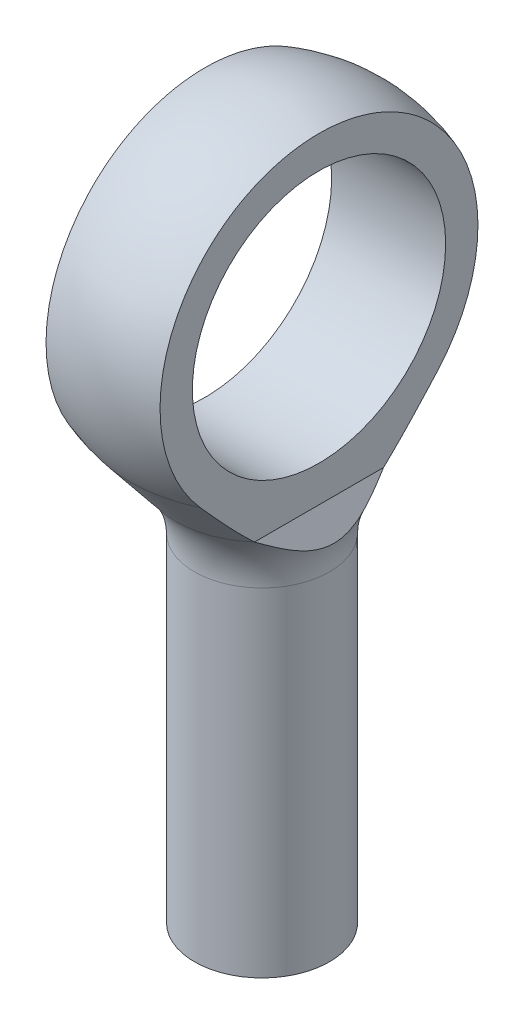
SolidWorks part; units mm, degrees
ref_plane "Front Plane" through (0, 0, 0) normal (0, 0, 1) x (1, 0, 0)
ref_plane "Top Plane" through (0, 0, 0) normal (0, 1, 0) x (1, 0, 0)
ref_plane "Right Plane" through (0, 0, 0) normal (1, 0, 0) x (0, 0, -1)
sketch "Sketch1" plane through (0, 0, 0) normal (0, 0, 1) x (1, 0, 0)
  line L0 (0, 0) -> (0, 7819.097) construction
  line L1 (5.0982, 23.1266) -> (7.8037, 26.5029)
  line L2 (4, 0) -> (-4, 0) construction
  line L3 (4, 0) -> (4, 20)
  line L4 (4, 21.7562) -> (-4, 21.7562) construction
  line L5 (-4, 0) -> (-4, 20)
  line L6 (-5.0982, 23.1266) -> (-7.8037, 26.5029)
  line L7 (0, 42.7562) -> (0, 0)
  line L8 (-4, 0) -> (4, 0)
  arc A0 (7.8037, 26.5029) -> (-7.8037, 26.5029) centre (0, 32.7562) ccw
  arc A1 (4, 20) -> (5.0982, 23.1266) centre (9, 20) cw
  arc A2 (-4, 20) -> (-5.0982, 23.1266) centre (-9, 20) ccw
  point P7 (0, 0)
  dimension "D1" = 20
  dimension "D5" = 5
  dimension "D2" = 8
  dimension "D3" = 20
  dimension "D4" = 11
revolve "Revolve2" add sketch "Sketch1" angle 360 about L0
sketch "Sketch2" plane through (0, 0, 0) normal (0, 0, 1) x (1, 0, 0)
  line L0 (-20, 42.7562) -> (20, 42.7562)
  line L1 (20, 42.7562) -> (20, -5.6687)
  line L2 (20, -5.6687) -> (3.375, 23.1266)
  line L3 (3.375, 23.1266) -> (3.375, 42.7562)
  line L4 (-20, 42.7562) -> (-20, -5.6687)
  line L5 (-20, -5.6687) -> (-3.375, 23.1266)
  line L6 (-3.375, 23.1266) -> (-3.375, 42.7562)
  line L7 (0, 0) -> (0, 50000) construction
  line L8 (-4, 0) -> (4, 0) construction
  line L9 (5.0982, 23.1266) -> (-5.0982, 23.1266) construction
  arc A0 (7.8037, 26.5029) -> (-7.8037, 26.5029) centre (0, 32.7562) ccw construction
  point P23 (0, 0)
  dimension "D1" = 3.375
  dimension "D2" = 3.375
  dimension "D3" = 150
  dimension "D4" = 150
  dimension "D5" = 40
  dimension "D6" = 20
extrude "Cut-Extrude4" cut sketch "Sketch2" against normal through all both and the other way through all contours L5 L6 L0 L4 | L3 L2 L1 L0
sketch "Sketch3" plane through (3.375, 0, 0) normal (1, 0, 0) x (0, 0, -1)
  line L0 (0, 38.0843) -> (0, 22.0999) construction
  circle A0 centre (0, 32.7562) radius 7.5
  arc A4 (7.0361, 26.5029) -> (-7.0361, 26.5029) centre (0, 32.7562) ccw construction
  dimension "D1" = 15
extrude "Cut-Extrude5" cut sketch "Sketch3" against normal blind 24
sketch "Sketch5" plane through (0, 0, 0) normal (0, -1, 0) x (1, 0, 0)
  circle A0 centre (0, 0) radius 3
  dimension "D1" = 6
extrude "Cut-Extrude6" cut sketch "Sketch5" against normal blind 12.7
